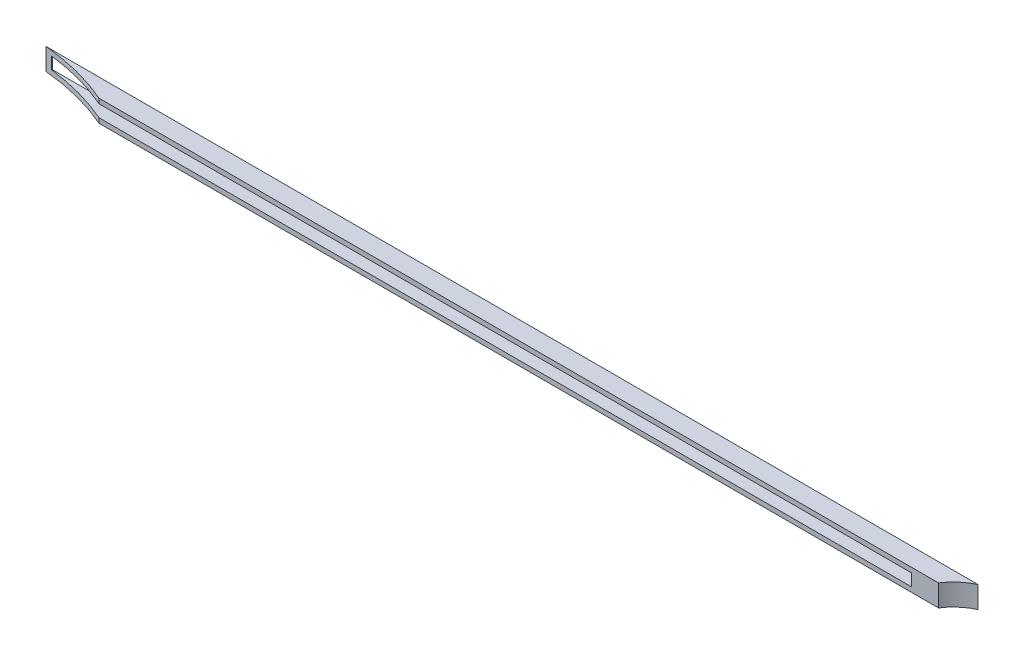
SolidWorks part; units mm, degrees
ref_plane "Front Plane" through (0, 0, 0) normal (0, 0, 1) x (1, 0, 0)
ref_plane "Top Plane" through (0, 0, 0) normal (0, 1, 0) x (1, 0, 0)
ref_plane "Right Plane" through (0, 0, 0) normal (1, 0, 0) x (0, 0, -1)
sketch "Sketch1" plane through (0, 0, 0) normal (0, 0, 1) x (1, 0, 0)
  line L1 (-256.2037, 5.715) -> (256.2037, 5.715)
  line L2 (-256.2037, 5.715) -> (-256.2037, -5.715)
  line L3 (-256.2037, -5.715) -> (256.2037, -5.715)
  line L4 (256.2037, 5.715) -> (256.2037, -5.715)
  line L5 (-256.2037, 5.715) -> (256.2037, -5.715) construction
  line L6 (-256.2037, -5.715) -> (256.2037, 5.715) construction
  line L7 (-230.8037, 3.175) -> (230.8037, 3.175)
  line L8 (-230.8037, 3.175) -> (-230.8037, -3.175)
  line L9 (-230.8037, -3.175) -> (230.8037, -3.175)
  line L10 (230.8037, 3.175) -> (230.8037, -3.175)
  line L11 (-230.8037, 3.175) -> (230.8037, -3.175) construction
  line L12 (-230.8037, -3.175) -> (230.8037, 3.175) construction
  point P0 (0, 0)
  point P6 (0, 0)
  point P11 (-230.8037, 0)
  dimension "D1" = 11.43
  dimension "D2" = 6.35
  dimension "D3" = 512.4074
  dimension "D4" = 25.4
extrude "Boss-Extrude1" add sketch "Sketch1" along normal blind 9.652
sketch "Sketch2" plane through (0, 5.715, 0) normal (0, 1, 0) x (1, 0, 0)
  circle A0 centre (-245.1841, -120.8301) radius 121.3315
  circle A1 centre (267.3382, -24.0848) radius 26.534
  point P6 (267.3382, -24.0848)
  dimension "D1" = 242.663
  dimension "D2" = 53.068
  dimension "D3" = 521.5734
extrude "Cut-Extrude1" cut sketch "Sketch2" against normal through all both and the other way through all
